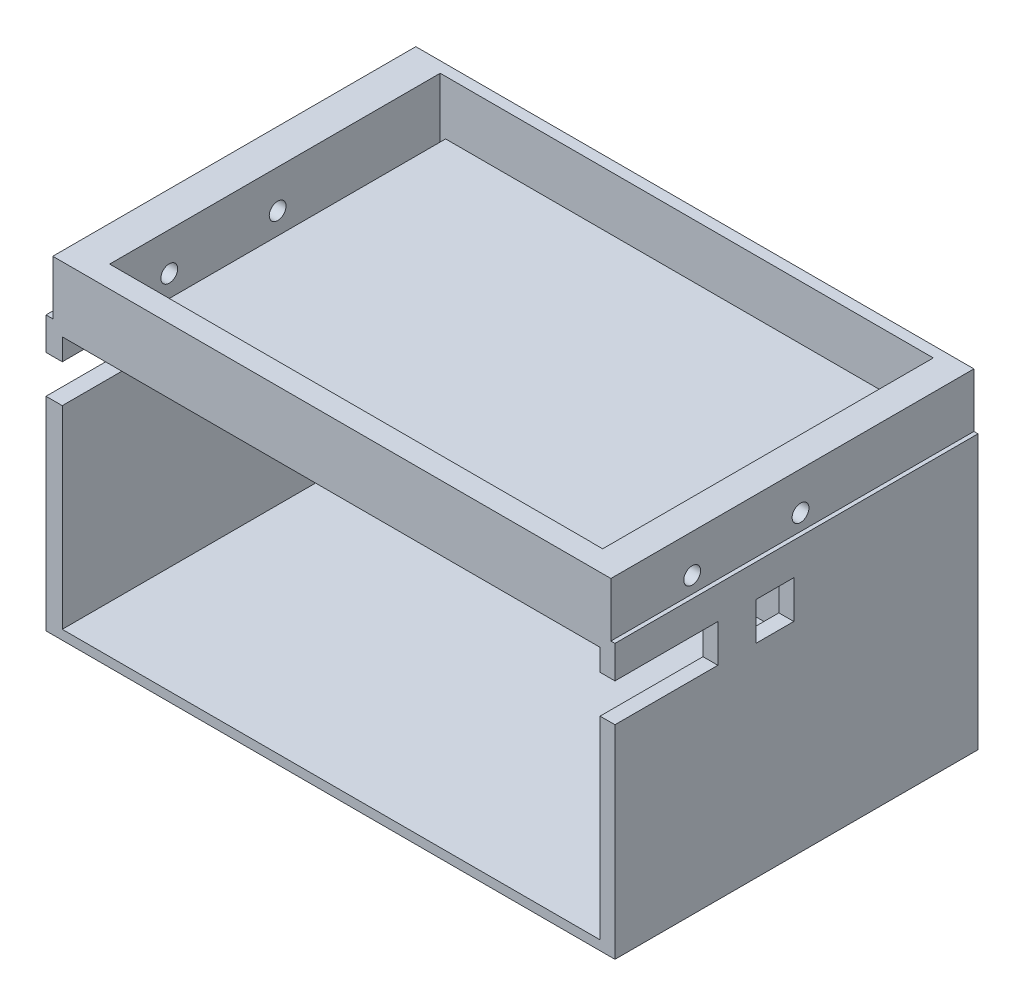
SolidWorks part; units mm, degrees
ref_plane "前视基准面" through (0, 0, 0) normal (0, 0, 1) x (1, 0, 0)
ref_plane "上视基准面" through (0, 0, 0) normal (0, 1, 0) x (1, 0, 0)
ref_plane "右视基准面" through (0, 0, 0) normal (1, 0, 0) x (0, 0, -1)
sketch "草图1" plane through (0, 0, 0) normal (0, 1, 0) x (1, 0, 0)
  line L1 (-49.5, 32.5) -> (49.5, 32.5)
  line L2 (-49.5, 32.5) -> (-49.5, -32.5)
  line L3 (-49.5, -32.5) -> (49.5, -32.5)
  line L4 (49.5, 32.5) -> (49.5, -32.5)
  line L5 (-49.5, 32.5) -> (49.5, -32.5) construction
  line L6 (-49.5, -32.5) -> (49.5, 32.5) construction
  point P0 (0, 0)
  dimension "D1" = 99
  dimension "D2" = 65
extrude "凸台-拉伸1" add sketch "草图1" along normal blind 2
ref_plane "基准面1" through (0, 2, 0) normal (0, 1, 0) x (1, 0, 0)
sketch "草图2" plane through (0, 2, 0) normal (0, 1, 0) x (1, 0, 0)
  line L0 (-49.5, 32.5) -> (-49.5, -32.5) construction
  line L1 (-52.5, -32.5) -> (52.5, -32.5)
  line L2 (-52.5, -32.5) -> (-52.5, 34.5)
  line L3 (-52.5, 34.5) -> (52.5, 34.5)
  line L4 (52.5, -32.5) -> (52.5, 34.5)
  line L5 (49.5, -32.5) -> (49.5, 32.5) construction
  line L6 (49.5, 32.5) -> (-49.5, 32.5) construction
  line L8 (-49.5, 32.5) -> (49.5, 32.5)
  line L9 (-49.5, 32.5) -> (-49.5, -32.5)
  line L10 (-49.5, -32.5) -> (49.5, -32.5)
  line L11 (49.5, 32.5) -> (49.5, -32.5)
  dimension "D1" = 3
  dimension "D2" = 3
  dimension "D3" = 2
  dimension "D4" = 67
extrude "凸台-拉伸2" add sketch "草图2" along normal blind 46.5 and the other way blind 2 contours L8 L11 L1 L4 L3 L2 L9
ref_plane "基准面2" through (0, 48.5, 0) normal (0, 1, 0) x (1, 0, 0)
sketch "草图3" plane through (0, 48.5, 0) normal (0, 1, 0) x (1, 0, 0)
  line L1 (-52.5, -32.5) -> (52.5, -32.5)
  line L2 (-52.5, -32.5) -> (-52.5, 34.5)
  line L3 (-52.5, 34.5) -> (52.5, 34.5)
  line L4 (52.5, -32.5) -> (52.5, 34.5)
extrude "凸台-拉伸3" add sketch "草图3" along normal blind 2
ref_plane "基准面3" through (0, 50.5, 0) normal (0, 1, 0) x (1, 0, 0)
sketch "草图5" plane through (0, 50.5, 0) normal (0, 1, 0) x (1, 0, 0)
  line L0 (52.5, 34.5) -> (-52.5, 34.5) construction
  line L1 (-51.25, 34.5) -> (-43.75, 34.5)
  line L2 (-51.25, 34.5) -> (-51.25, -32.5)
  line L3 (-51.25, -32.5) -> (-43.75, -32.5)
  line L4 (-43.75, 34.5) -> (-43.75, -32.5)
  line L5 (-52.5, -32.5) -> (52.5, -32.5) construction
  line L6 (52.5, -32.5) -> (52.5, 34.5) construction
  line L7 (44.25, 34.5) -> (51.75, 34.5)
  line L8 (44.25, 34.5) -> (44.25, -32.5)
  line L9 (44.25, -32.5) -> (51.75, -32.5)
  line L10 (51.75, 34.5) -> (51.75, -32.5)
  line L12 (-51.25, 34.5) -> (51.75, 34.5)
  line L13 (-51.25, 34.5) -> (-51.25, 32.5)
  line L14 (-51.25, 32.5) -> (51.75, 32.5)
  line L15 (51.75, 34.5) -> (51.75, 32.5)
  line L16 (-51.25, -32.5) -> (51.75, -32.5)
  line L17 (-51.25, -32.5) -> (-51.25, -28.5)
  line L18 (-51.25, -28.5) -> (51.75, -28.5)
  line L19 (51.75, -32.5) -> (51.75, -28.5)
  dimension "D1" = 7.5
  dimension "D2" = 7.5
  dimension "D3" = 103
  dimension "D4" = 0.75
  dimension "D5" = 2
  dimension "D6" = 4
extrude "凸台-拉伸4" add sketch "草图5" along normal blind 10 contours L2 L14 L4 L1 | L4 L14 L8 L12 | L14 L2 L3 L4 | L8 L14 L10 L7 | L14 L8 L9 L10 | L17 L16 L19 L18
ref_plane "基准面4" through (-52.5, 0, 0) normal (-1, 0, 0) x (0, 0, 1)
sketch "草图7" plane through (-52.5, 0, 0) normal (-1, 0, 0) x (0, 0, 1)
  line L0 (55, 48.5) -> (-55, 48.5) construction
  line L1 (-0.5, 44.5) -> (6.5, 44.5)
  line L2 (-0.5, 44.5) -> (-0.5, 37.5)
  line L3 (-0.5, 37.5) -> (6.5, 37.5)
  line L4 (6.5, 44.5) -> (6.5, 37.5)
  line L5 (32.5, 0) -> (32.5, 50.5) construction
  line L7 (13.5, 37.5) -> (37.9957, 37.5)
  line L8 (13.5, 37.5) -> (13.5, 44.5)
  line L9 (13.5, 44.5) -> (37.9957, 44.5)
  line L10 (37.9957, 37.5) -> (37.9957, 44.5)
  dimension "D1" = 4
  dimension "D2" = 7
  dimension "D3" = 7
  dimension "D4" = 26
  dimension "D5" = 7
  dimension "D7" = 7
extrude "切除-拉伸1" cut sketch "草图7" against normal through all
ref_plane "基准面5" through (-51.25, 0, 0) normal (-1, 0, 0) x (0, 0, 1)
sketch "草图8" plane through (-52.5, 0, 0) normal (-1, 0, 0) x (0, 0, 1)
  line L0 (32.5, 60.5) -> (32.5, 50.5) construction
  line L1 (0.4125, 50.5) -> (-0.4125, 50.5) construction
  circle A0 centre (17.5, 53.5) radius 1.55
  circle A1 centre (-2.5, 53.5) radius 1.55
  dimension "D1" = 3.1
  dimension "D2" = 3.1
  dimension "D3" = 15
  dimension "D4" = 20
  dimension "D5" = 3
  dimension "D6" = 3
extrude "切除-拉伸2" cut sketch "草图8" against normal through all
ref_plane "基准面6" through (0, 0, 32.5) normal (0, 0, 1) x (1, 0, 0)
sketch "草图9" plane through (0, 0, 32.5) normal (0, 0, 1) x (1, 0, 0)
  line L0 (49.5, 2) -> (49.5, 37.5) construction
  line L1 (-49.5, 48.5) -> (49.75, 48.5)
  line L2 (-49.5, 48.5) -> (-49.5, 1.75)
  line L3 (-49.5, 1.75) -> (49.75, 1.75)
  line L4 (49.75, 48.5) -> (49.75, 1.75)
  line L5 (35.75, 2) -> (-35.75, 2) construction
  dimension "D1" = 0.25
  dimension "D2" = 0.25
extrude "切除-拉伸3" cut sketch "草图9" against normal blind 66
sketch "草图10" plane through (0, 0, 32.5) normal (0, 0, 1) x (1, 0, 0)
  circle A0 centre (0, 21.302) radius 4
  dimension "D1" = 8
extrude "切除-拉伸4" cut sketch "草图10" against normal through all
ref_plane "基准面7" through (0, 60.5, 0) normal (0, 1, 0) x (1, 0, 0)
sketch "草图11" plane through (0, 60.5, 0) normal (0, 1, 0) x (1, 0, 0)
  line L0 (-43.75, 32.5) -> (44.25, 32.5) construction
  line L1 (44.25, 32.5) -> (46.25, 32.5)
  line L2 (44.25, 32.5) -> (44.25, -28.5227)
  line L3 (44.25, -28.5227) -> (46.25, -28.5227)
  line L4 (46.25, 32.5) -> (46.25, -28.5227)
  line L5 (-43.75, -28.5) -> (-44.75, -28.5)
  line L6 (-43.75, -28.5) -> (-43.75, 32.5)
  line L7 (-43.75, 32.5) -> (-44.75, 32.5)
  line L8 (-44.75, -28.5) -> (-44.75, 32.5)
  dimension "D1" = 2
  dimension "D2" = 1
extrude "切除-拉伸5" cut sketch "草图11" against normal up to next
